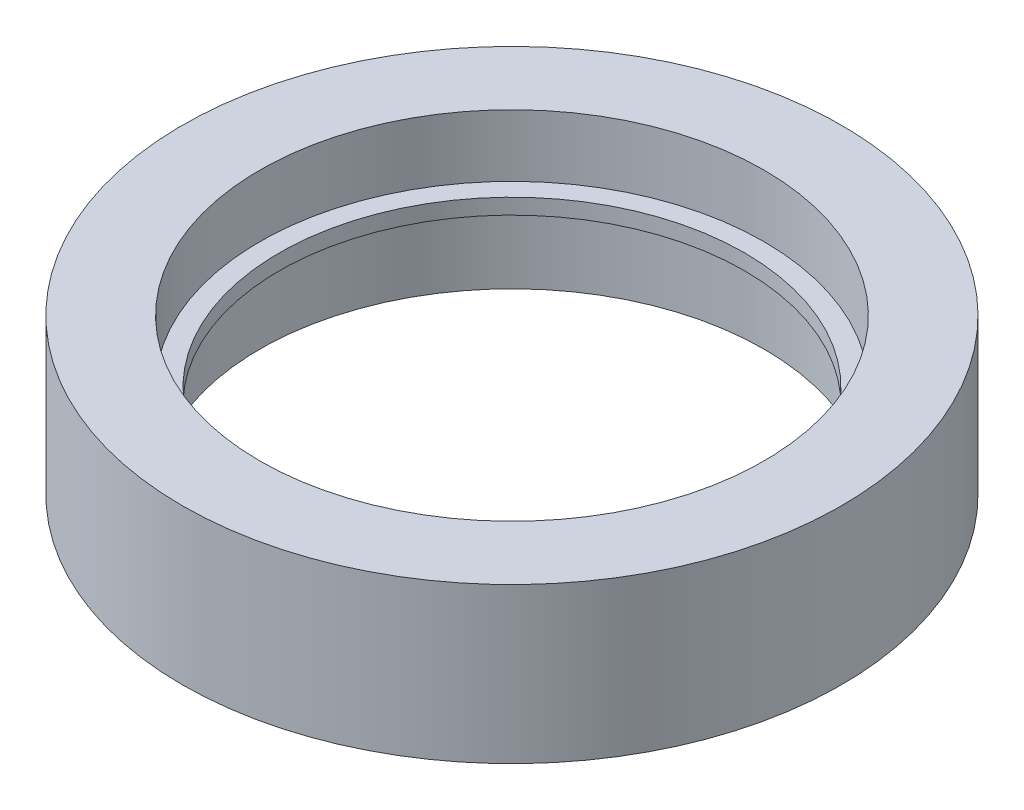
SolidWorks part; units mm, degrees
ref_plane "Front Plane" through (0, 0, 0) normal (0, 0, 1) x (1, 0, 0)
ref_plane "Top Plane" through (0, 0, 0) normal (0, 1, 0) x (1, 0, 0)
ref_plane "Right Plane" through (0, 0, 0) normal (1, 0, 0) x (0, 0, -1)
sketch "Sketch1" plane through (0, 0, 0) normal (0, 1, 0) x (1, 0, 0)
  circle A0 centre (0, 0) radius 32.5
  circle A1 centre (0, 0) radius 42.5
  dimension "D1" = 65
  dimension "D2" = 85
extrude "Boss-Extrude1" add sketch "Sketch1" along normal blind 20
ref_plane "Plane1" through (0, 10, 0) normal (0, 1, 0) x (1, 0, 0)
sketch "Sketch2" plane through (0, 10, 0) normal (0, 1, 0) x (1, 0, 0)
  circle A0 centre (0, 0) radius 33
  circle A1 centre (0, 0) radius 30
  dimension "D1" = 66
  dimension "D2" = 60
extrude "Boss-Extrude2" add sketch "Sketch2" along normal blind 2
